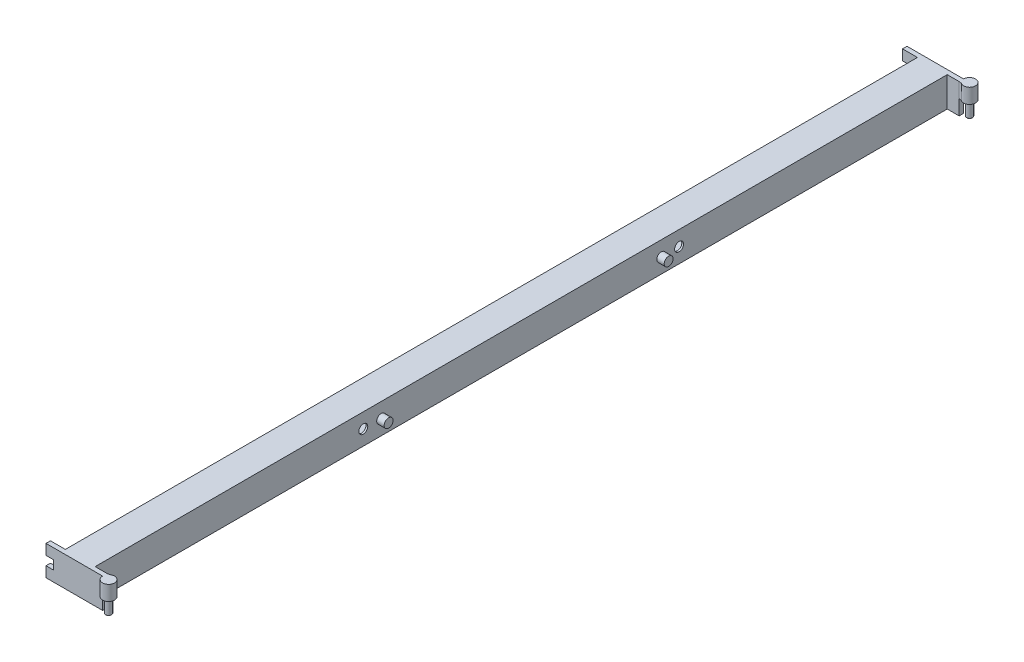
SolidWorks part; units mm, degrees
ref_plane "Front Plane" through (0, 0, 0) normal (0, 0, 1) x (1, 0, 0)
ref_plane "Top Plane" through (0, 0, 0) normal (0, 1, 0) x (1, 0, 0)
ref_plane "Right Plane" through (0, 0, 0) normal (1, 0, 0) x (0, 0, -1)
sketch "Sketch1" plane through (0, 0, 0) normal (0, 0, 1) x (1, 0, 0)
  line L0 (8.8, -83.2) -> (-8.8, -83.2)
  line L1 (10, -82) -> (-10, -82)
  line L2 (10, -82) -> (10, -102)
  line L3 (10, -102) -> (-10, -102)
  line L4 (-10, -82) -> (-10, -102)
  line L5 (-8.8, -83.2) -> (-8.8, -100.8)
  line L6 (8.8, -100.8) -> (-8.8, -100.8)
  line L7 (8.8, -83.2) -> (8.8, -100.8)
  dimension "D1" = 20
  dimension "D2" = 1.2
extrude "Boss-Extrude1" add sketch "Sketch1" along normal offset from surface 3 and the other way offset from surface (286 mm away) 3
sketch "Sketch2" plane through (0, 0, -286) normal (0, 0, -1) x (-1, 0, 0)
  line L1 (18, -102) -> (-18, -102)
  line L2 (18, -102) -> (18, -82)
  line L3 (18, -82) -> (-18, -82)
  line L4 (-18, -102) -> (-18, -82)
  line L6 (15, -83.742) -> (15, -98.8183) construction
  line L7 (15, -1876) -> (15, 0) construction
  line L8 (-15, -87.5402) -> (-15, -95.5339) construction
  line L9 (-15, 0) -> (-15, -1876) construction
  dimension "D1" = 3
  dimension "D2" = 3
extrude "Boss-Extrude2" add sketch "Sketch2" along normal up to surface (575 mm away)
sketch "Sketch3" plane through (10, 0, 0) normal (1, 0, 0) x (0, 0, -1)
  circle A0 centre (-106, -92) radius 3
  circle A1 centre (-94, -92) radius 3
  circle A2 centre (94, -92) radius 3
  circle A3 centre (106, -92) radius 3
extrude "Cut-Extrude1" cut sketch "Sketch3" against normal through all
sketch "Sketch4" plane through (0, -82, 0) normal (0, 1, 0) x (1, 0, 0)
  line L0 (18, 289) -> (20.4869, 289) construction
  line L2 (18, 286) -> (19.7229, 285.7114)
  line L3 (18, 289) -> (18, 286)
  arc A0 (19.7229, 285.7114) -> (18, 289) centre (22, 289) ccw
  dimension "D1" = 8
extrude "Boss-Extrude3" add sketch "Sketch4" against normal blind 10
sketch "Sketch5" plane through (0, -92, 0) normal (0, -1, 0) x (1, 0, 0)
  circle A0 centre (22, -289) radius 2
  dimension "D1" = 4
extrude "Boss-Extrude4" add sketch "Sketch5" along normal blind 10
chamfer "Chamfer1" distance 0.5 angle 45 1 edges at (22, -102, -291)
sketch "Sketch6" plane through (0, 0, 286) normal (0, 0, 1) x (1, 0, 0)
  line L1 (-18, -82) -> (18, -82)
  line L2 (-18, -82) -> (-18, -102)
  line L3 (-18, -102) -> (18, -102)
  line L4 (18, -82) -> (18, -102)
extrude "Boss-Extrude5" add sketch "Sketch6" along normal up to surface (3 mm away)
mirror "Mirror5" about plane through (0, 0, 0) normal (0, 0, 1) of "Boss-Extrude4", "Boss-Extrude3"
chamfer "Chamfer2" distance 0.5 angle 45 1 edges at (22, -102, 291)
sketch "Sketch7" plane through (-18, 0, 0) normal (-1, 0, 0) x (0, 0, 1)
  line L5 (289, -102) -> (289, -82)
  line L6 (289, -82) -> (286, -82)
  line L7 (286, -82) -> (286, -102)
  line L8 (286, -102) -> (289, -102)
  line L9 (289, -102) -> (289, -82)
  line L10 (289, -82) -> (286, -82)
  line L11 (286, -82) -> (286, -102)
  line L12 (286, -102) -> (289, -102)
  dimension "D1" = 0
extrude "Boss-Extrude6" add sketch "Sketch7" along normal blind 2
sketch "Sketch8" plane through (-20, 0, 0) normal (-1, 0, 0) x (0, 0, 1)
  line L0 (286, -82) -> (286, -102) construction
  line L1 (286, -95) -> (289, -95)
  line L2 (286, -95) -> (286, -89)
  line L3 (286, -89) -> (289, -89)
  line L4 (289, -95) -> (289, -89)
  line L5 (289, -102) -> (289, -82) construction
  line L6 (286, -102) -> (289, -102) construction
  dimension "D1" = 6
  dimension "D2" = 7
extrude "Cut-Extrude2" cut sketch "Sketch8" against normal blind 5
mirror "Mirror6" about plane through (0, 0, 0) normal (0, 0, 1) of "Cut-Extrude2", "Boss-Extrude6"
sketch "Sketch9" plane through (-10, 0, 0) normal (-1, 0, 0) x (0, 0, 1)
  circle A0 centre (94, -92) radius 3 construction
  circle A1 centre (94, -92) radius 3
  circle A2 centre (-94, -92) radius 3 construction
  circle A3 centre (-94, -92) radius 3
extrude "Boss-Extrude7" add sketch "Sketch9" against normal blind 25 and the other way blind 2
